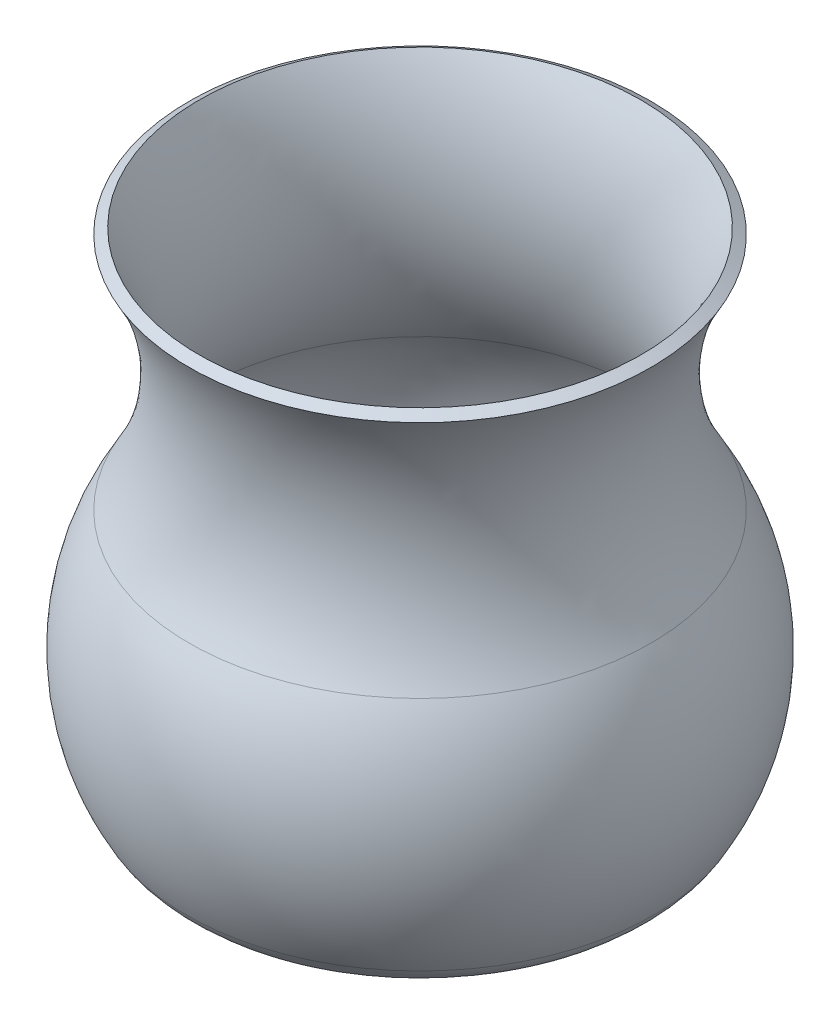
SolidWorks part; units mm, degrees
ref_plane "Front Plane" through (0, 0, 0) normal (0, 0, 1) x (1, 0, 0)
ref_plane "Top Plane" through (0, 0, 0) normal (0, 1, 0) x (1, 0, 0)
ref_plane "Right Plane" through (0, 0, 0) normal (1, 0, 0) x (0, 0, -1)
sketch "Sketch1" plane through (0, 0, 0) normal (0, 0, 1) x (1, 0, 0)
  line L0 (0, 0) -> (24.2874, 0)
  line L1 (0, 0) -> (0, 71.519) construction
  arc A0 (30.3619, 3.5213) -> (30, 33.9533) centre (4.3285, 18.4299) ccw
  arc A1 (30, 33.9533) -> (30, 65) centre (55.6715, 49.4766) cw
  arc A2 (24.2874, 0) -> (30.3619, 3.5213) centre (24.2874, 7) ccw
  point P7 (57.1687, 92.0054)
  point P9 (44.9038, 48.8762)
  point P10 (53.5297, 83.2448)
  point P11 (47.195, 47.124)
  point P12 (0, 0)
  point P13 (0, 0)
  point P14 (0, 0)
  point P15 (50.7754, 42.272)
  point P16 (50.7754, 37.8243)
  point P17 (56.6296, 35.1287)
  point P18 (53.5297, 34.4548)
  point P19 (52.721, 35.533)
  point P20 (0, 0)
  point P21 (52.5862, 35.533)
  point P22 (31.5607, 65)
  point P23 (28, 33.2418)
  point P24 (0, 71.519)
  point P27 (28, 0)
  dimension "D5" = 30
  dimension "D6" = 30
  dimension "D7" = 7
  dimension "D1" = 28
  dimension "D2" = 65
  dimension "D3" = 60
  dimension "D4" = 60
revolve "Revolve-Thin1" add sketch "Sketch1" angle 360 about L1 wall 1.5
